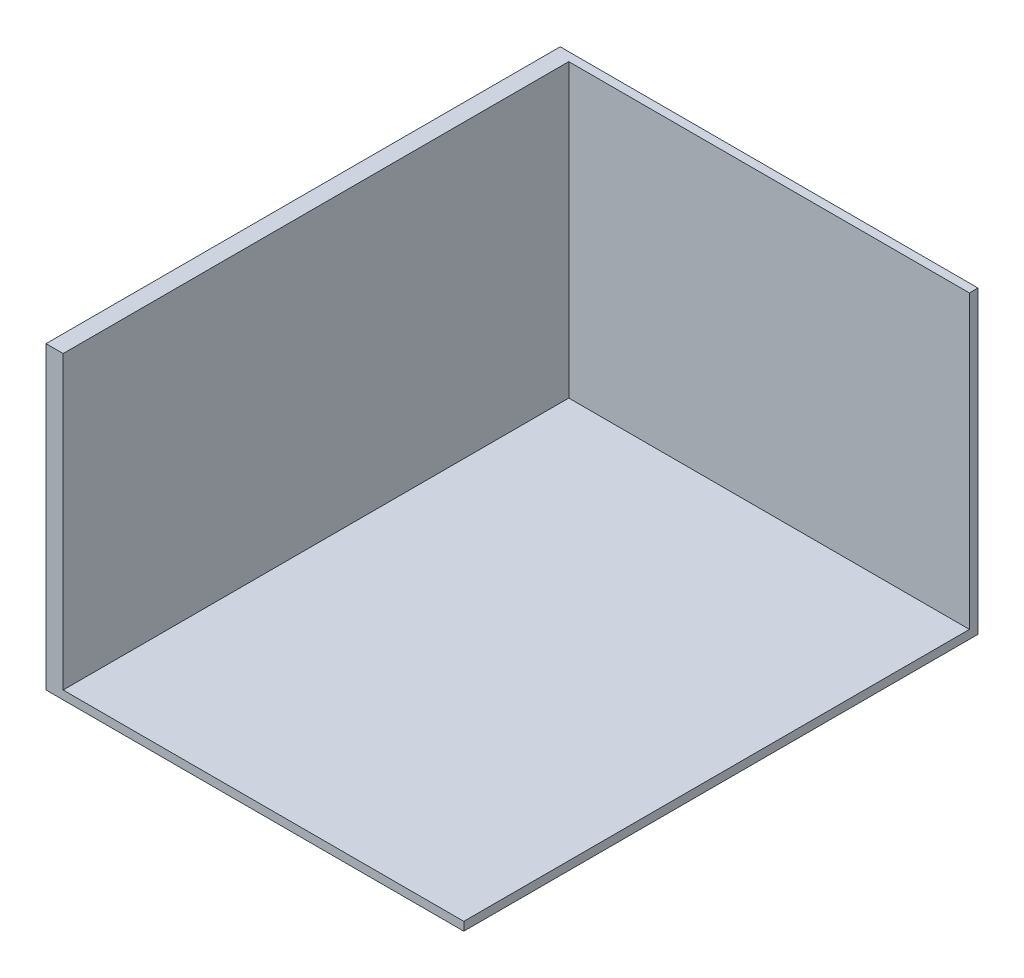
SolidWorks part; units mm, degrees
ref_plane "정면" through (0, 0, 0) normal (0, 0, 1) x (1, 0, 0)
ref_plane "윗면" through (0, 0, 0) normal (0, 1, 0) x (1, 0, 0)
ref_plane "우측면" through (0, 0, 0) normal (1, 0, 0) x (0, 0, -1)
sketch "스케치2" plane through (0, 0, 0) normal (0, 1, 0) x (1, 0, 0)
  line L1 (-48.75, 60) -> (48.75, 60)
  line L2 (-48.75, 60) -> (-48.75, -60)
  line L3 (-48.75, -60) -> (48.75, -60)
  line L4 (48.75, 60) -> (48.75, -60)
  line L5 (-48.75, 60) -> (48.75, -60) construction
  line L6 (-48.75, -60) -> (48.75, 60) construction
  point P0 (0, 0)
  dimension "D1" = 97.5
  dimension "D2" = 120
extrude "보스-돌출2" add sketch "스케치2" along normal blind 2
sketch "스케치3" plane through (0, 2, 0) normal (0, 1, 0) x (1, 0, 0)
  line L0 (48.75, -60) -> (48.75, 60) construction
  line L1 (-48.75, 60) -> (48.75, 60)
  line L2 (-48.75, 60) -> (-48.75, 58)
  line L3 (-48.75, 58) -> (48.75, 58)
  line L4 (48.75, 60) -> (48.75, 58)
  dimension "D1" = 2
extrude "보스-돌출3" add sketch "스케치3" along normal blind 68
sketch "스케치7" plane through (0, 2, 0) normal (0, 1, 0) x (1, 0, 0)
  line L0 (-48.75, -60) -> (48.75, -60) construction
  line L1 (-48.75, 58) -> (-44.75, 58)
  line L2 (-48.75, 58) -> (-48.75, -60)
  line L3 (-48.75, -60) -> (-44.75, -60)
  line L4 (-44.75, 58) -> (-44.75, -60)
  dimension "D1" = 4
extrude "보스-돌출6" add sketch "스케치7" along normal blind 68
sketch "스케치8" plane through (-48.75, 0, 0) normal (-1, 0, 0) x (0, 0, 1)
  line L0 (-60, 0) -> (60, 0) construction
  line L1 (-15.25, 31.5) -> (15.25, 31.5)
  line L2 (-15.25, 31.5) -> (-15.25, 1)
  line L3 (-15.25, 1) -> (15.25, 1)
  line L4 (15.25, 31.5) -> (15.25, 1)
  line L5 (-60, 70) -> (-60, 0) construction
  dimension "D1" = 30.5
  dimension "D2" = 30.5
  dimension "D3" = 1
  dimension "D4" = 44.75
extrude "컷-돌출1" cut sketch "스케치8" against normal blind 2
